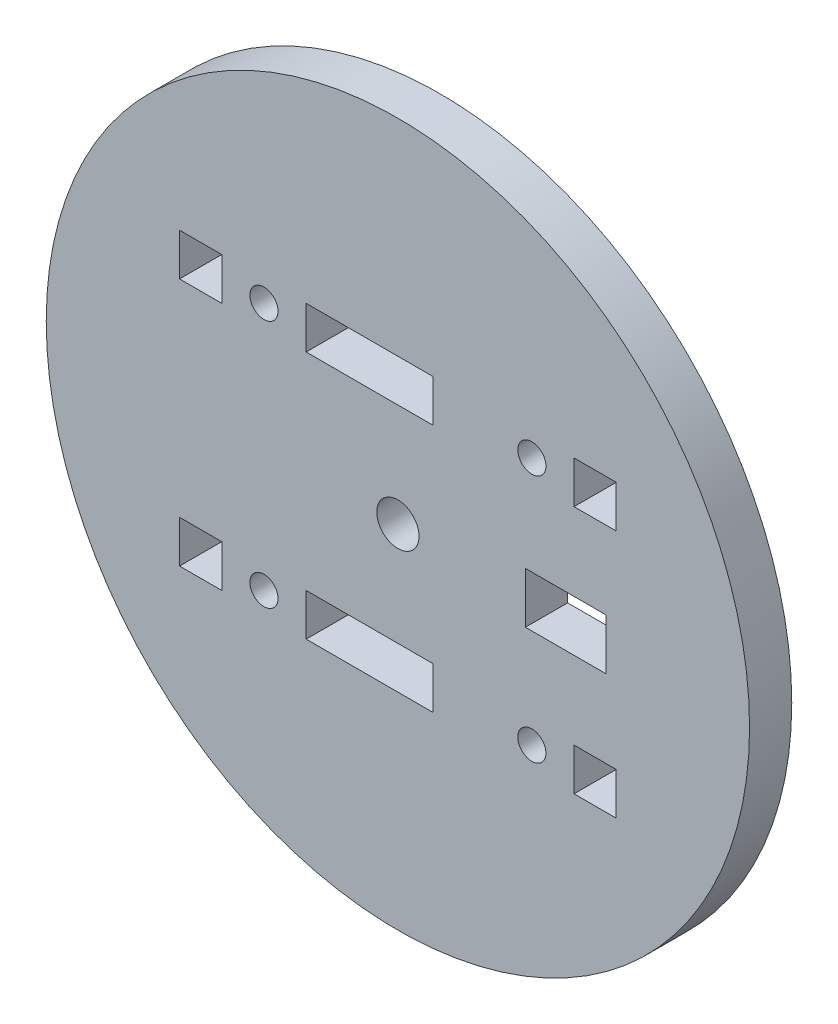
SolidWorks part; units mm, degrees
material "Balsa"
ref_plane "Plan de face" through (0, 0, 0) normal (0, 0, 1) x (1, 0, 0)
ref_plane "Plan de dessus" through (0, 0, 0) normal (0, 1, 0) x (1, 0, 0)
ref_plane "Plan de droite" through (0, 0, 0) normal (1, 0, 0) x (0, 0, -1)
sketch "Esquisse1" plane through (0, 0, 0) normal (0, 0, 1) x (1, 0, 0)
  circle A0 centre (0, 0) radius 125
  dimension "D1" = 250
extrude "Boss.-Extru.1" add sketch "Esquisse1" along normal blind 15
sketch "Esquisse2" plane through (0, 0, 15) normal (0, 0, 1) x (1, 0, 0)
  line L0 (-88.3883, 88.3883) -> (88.3883, -88.3883) construction
  line L1 (-125, 0) -> (125, 0) construction
  line L2 (0, 125) -> (0, -125) construction
  line L3 (88.3883, 88.3883) -> (-88.3883, -88.3883) construction
  line L4 (88.3883, 0) -> (88.3883, -88.3883) construction
  line L5 (-88.3883, 88.3883) -> (-88.3883, 0) construction
  line L6 (-88.3883, 44.1942) -> (116.9268, 44.1942) construction
  line L7 (88.3883, -44.1942) -> (-116.9268, -44.1942) construction
  line L8 (88.3883, 88.3883) -> (88.3883, 0) construction
  line L9 (-88.3883, 0) -> (-88.3883, -88.3883) construction
  line L10 (62.6103, 51.6942) -> (62.6103, 36.6942)
  line L11 (-77.6103, 36.6942) -> (-62.6103, 36.6942)
  line L12 (-77.6103, 36.6942) -> (-77.6103, 51.6942)
  line L13 (-77.6103, 51.6942) -> (-62.6103, 51.6942)
  line L14 (77.6103, 36.6942) -> (77.6103, 51.6942)
  line L15 (-77.6103, 36.6942) -> (77.6103, 51.6942) construction
  line L16 (-77.6103, 51.6942) -> (77.6103, 36.6942) construction
  line L18 (45.3283, -9.06) -> (73.9683, -9.06)
  line L19 (45.3283, -9.06) -> (45.3283, 9.06)
  line L20 (45.3283, 9.06) -> (73.9683, 9.06)
  line L21 (73.9683, -9.06) -> (73.9683, 9.06)
  line L22 (45.3283, -9.06) -> (73.9683, 9.06) construction
  line L23 (-62.6103, 51.6942) -> (-62.6103, 36.6942)
  line L24 (-32.6103, 51.6942) -> (-32.6103, 36.6942)
  line L25 (12.3897, 51.6942) -> (12.3897, 36.6942)
  line L26 (-32.6103, 51.6942) -> (12.3897, 51.6942)
  line L27 (-32.6103, 36.6942) -> (12.3897, 36.6942)
  line L28 (62.6103, 36.6942) -> (77.6103, 36.6942)
  line L29 (62.6103, 51.6942) -> (77.6103, 51.6942)
  line L30 (45.3283, 9.06) -> (73.9683, -9.06) construction
  circle A0 centre (0, 0) radius 7.5
  circle A1 centre (0, 0) radius 125 construction
  circle A2 centre (47.6103, 44.1942) radius 5
  circle A3 centre (-47.6103, 44.1942) radius 5
  point P20 (0, 44.1942)
  point P25 (0, -44.1942)
  point P26 (59.6483, 0)
  dimension "D1" = 15
  dimension "D8" = 10
  dimension "D7" = 15
  dimension "D10" = 10
  dimension "D2" = 45
  dimension "D3" = 45
  dimension "D4" = 15
  dimension "D5" = 155.2205
  dimension "D6" = 15
  dimension "D9" = 15
  dimension "D11" = 15
  dimension "D12" = 45
  dimension "D13" = 15
  dimension "D14" = 18.12
  dimension "D15" = 28.64
extrude "Enlèv. mat.-Extru.1" cut sketch "Esquisse2" against normal through all
mirror "Symétrie1" about plane through (0, 0, 0) normal (0, 1, 0) of "Enlèv. mat.-Extru.1"
